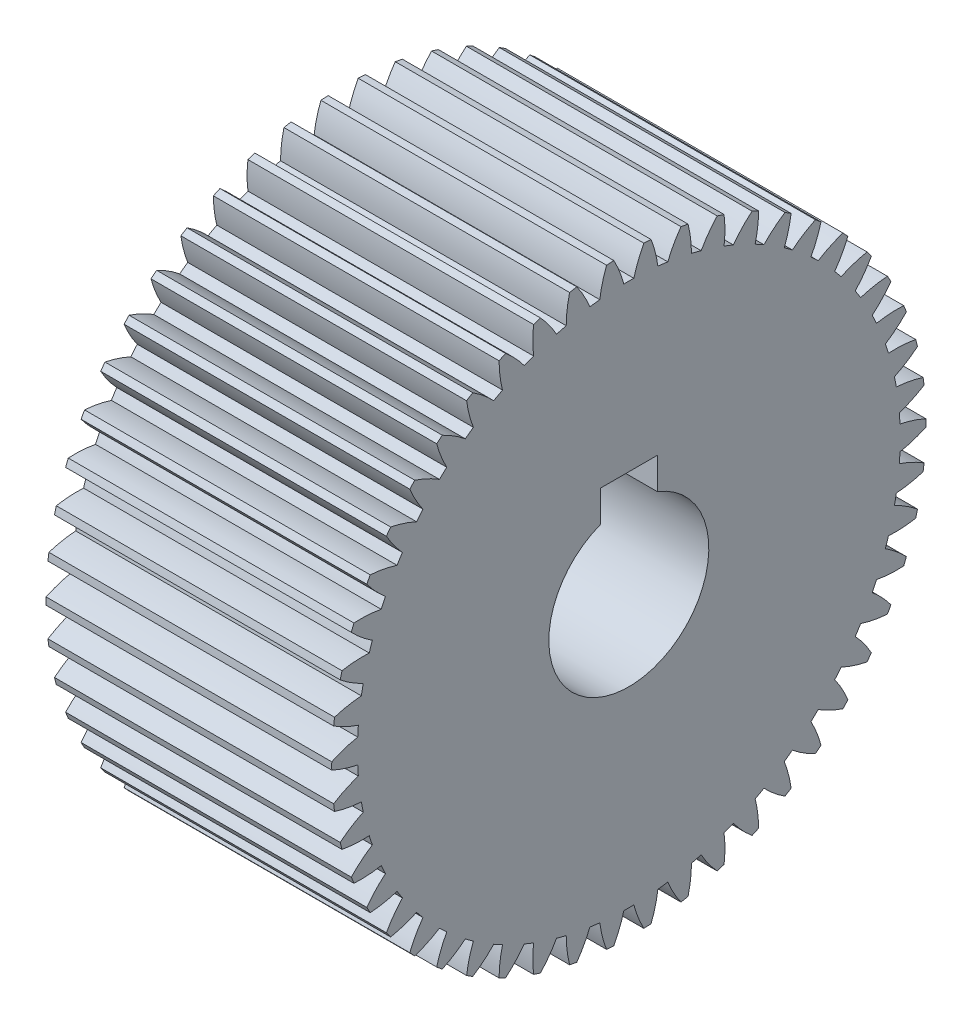
SolidWorks part; units mm, degrees
ref_plane "Plane1" through (0, 0, 0) normal (0, 0, 1) x (1, 0, 0)
ref_plane "Plane2" through (0, 0, 0) normal (0, 1, 0) x (1, 0, 0)
ref_plane "Plane3" through (0, 0, 0) normal (1, 0, 0) x (0, 0, -1)
other "Configuration Table"
sketch "HoldingSke" plane through (0, 0, 0) normal (0, 1, 0) x (1, 0, 0)
  line L0 (0, 0) -> (0.6428, -0.766)
  line L1 (-15, 0) -> (100, 0) construction
  line L2 (0, 0) -> (-2.1039, 2.3779)
  line L3 (0, 0) -> (-11.863, 4.5341)
  line L4 (0, 0) -> (5.5511, 6.6156)
  line L5 (0, 0) -> (-46.8476, -17.4728)
  line L6 (0, 0) -> (-20.7241, -13.9826)
  line L7 (-2.1039, 2.3779) -> (8.6586, 51.2059)
  line L8 (-76.2, 54.61) -> (-73.9, 54.61)
  line L9 (-71.009, 38.7566) -> (-53.1078, 45.2721)
  line L10 (-76.2, 71.12) -> (104.1128, 71.12)
  line L11 (0, 0) -> (-25, 0)
  line L12 (-76.2, 101.6) -> (-76.162, 101.6)
  line L13 (24.9733, 27.94) -> (52.9518, 28.4284)
  line L14 (24.9733, 27.94) -> (24.9743, 27.94)
  line L15 (24.9733, 27.94) -> (100.4006, 29.5858)
  line L16 (-63.627, -1) -> (-12.827, -1)
  circle A0 centre (0, 0) radius 7
  circle A1 centre (0, 0) radius 23.749
  circle A2 centre (0, 0) radius 37.5
  circle A3 centre (0, 0) radius 7
  dimension "MHD" = 47.498
  dimension "Hub_dia" = 75
  dimension "Bore" = 14
  dimension "MBD" = 14
  dimension "Num_teeth" = 50
  dimension "Pitch" = 1
  dimension "Overall_len" = 50
  dimension "Show_teeth" = 50
  dimension "Thickness" = 25
  dimension "OAL" = 50.0001
  dimension "T_dim" = 2.3
  dimension "Ap" = 20
  dimension "H" = 19.05
  dimension "Pitch_radius" = 180.3128
  dimension "Width" = 25
  dimension "Backlash" = 0.038
  dimension "Addendum_fac" = 1
  dimension "Dedendum_fac" = 1.25
  dimension "Clearance_fac" = 0.25
  dimension "Dedendum_add" = 0.001
  dimension "Module" = 1
sketch "BasProSke" plane through (0, 0, 0) normal (0, 1, 0) x (1, 0, 0)
  line L0 (-10, 0) -> (60, 0) construction
  line L1 (0, 0) -> (0, 26)
  line L2 (0, 0) -> (25, 0)
  line L3 (25, 0) -> (25, 26)
  line L4 (25, 26) -> (0, 26)
  dimension "Thickness" = 25
  dimension "Diameter" = 52
revolve "Base-Revolve" add sketch "BasProSke" angle 360 about L0
sketch "TooCutSke" plane through (0, 0, 0) normal (1, 0, 0) x (0, 0, -1)
  line L1 (0, 0) -> (0, 107) construction
  line L2 (0, 0) -> (-0.8518, 24.9855) construction
  line L3 (0, 0) -> (-3.1382, 49.8807) construction
  line L4 (-0.8518, 24.9855) -> (-1.5691, 24.9404) construction
  arc A0 (0.4377, 23.745) -> (-0.4377, 23.745) centre (0, 0) ccw
  arc A1 (1.3294, 25.9914) -> (-1.3294, 25.9914) centre (0, 0) ccw
  circle A2 centre (0, 0) radius 25 construction
  circle A3 centre (0, 0) radius 23.4923 construction
  arc A4 (-0.4377, 23.745) -> (-1.3294, 25.9914) centre (-10.1099, 21.2056) ccw
  arc A5 (1.3294, 25.9914) -> (0.4377, 23.745) centre (10.1099, 21.2056) ccw
  dimension "Root_dia" = 47.498
  dimension "Overcut_dia" = 52.0508
  dimension "Pitch_dia" = 50
  dimension "Base_dia" = 46.9846
  dimension "Flank_rad" = 10
  dimension "Half_ang" = 3.6
  dimension "Half_CT" = 0.7188
extrude "ToothCut" cut sketch "TooCutSke" along normal through all
fillet "Breaks" [suppressed] radius 0.02
fillet "RootFillets" [suppressed] radius 0.251
pattern_circular "TeethCuts" count 50 every 7.2 about axis through (-10, 0, 0) along (1, 0, 0) of "ToothCut", "RootFillets", "Breaks"
sketch "HubNeaOneSke" plane through (0, 0, 0) normal (-1, 0, 0) x (0, 0, 1)
  circle A0 centre (0, 0) radius 23.749
  dimension "Diameter" = 47.498
extrude "HubNearOne" [suppressed] add sketch "HubNeaOneSke" along normal blind 25.0001
sketch "HubNeaBotSke" plane through (0, 0, 0) normal (-1, 0, 0) x (0, 0, 1)
  circle A0 centre (0, 0) radius 23.749
  dimension "Diameter" = 47.498
extrude "HubNearBoth" [suppressed] add sketch "HubNeaBotSke" along normal blind 12.5
ref_plane "FarPln" through (25, 0, 0) normal (1, 0, 0) x (0, 0, -1)
sketch "HubFarSke" plane through (25, 0, 0) normal (1, 0, 0) x (0, 0, -1)
  circle A0 centre (0, 0) radius 23.749
  dimension "Diameter" = 47.498
extrude "HubFar" [suppressed] add sketch "HubFarSke" along normal blind 12.5
sketch "BorSke" plane through (0, 0, 0) normal (1, 0, 0) x (0, 0, -1)
  circle A0 centre (0, 0) radius 7
  dimension "Diameter" = 14
extrude "Bore" cut sketch "BorSke" along normal mid plane 100.0001
sketch "KeySke" plane through (0, 0, 0) normal (1, 0, 0) x (0, 0, -1)
  line L0 (-2.5, 0) -> (-2.5, 9.3)
  line L1 (-2.5, 9.3) -> (2.5, 9.3)
  line L2 (2.5, 9.3) -> (2.5, 0)
  line L3 (0, 0) -> (0, 34) construction
  line L4 (-2.5, 0) -> (2.5, 0)
  dimension "Offset" = 9.3
  dimension "Width" = 5
extrude "Keyway" cut sketch "KeySke" along normal mid plane 100.0001
pattern_circular "Keyway2" [suppressed] count 2 every 90 about axis through (-10, 0, 0) along (1, 0, 0)
sketch "Sketch1" plane through (0, 0, 0) normal (-1, 0, 0) x (0, 0, 1)
  circle A0 centre (0, 0) radius 25
  dimension "D1" = 50
sketch "Sketch2" plane through (25, 0, 0) normal (1, 0, 0) x (0, 0, -1)
  circle A0 centre (0, 0) radius 25
equation "' \"Module@HoldingSke\" = 6.35"
equation "' \"Num_teeth@HoldingSke\" = 12"
equation "' \"Ap@HoldingSke\" =  20"
equation "' \"Ap@HoldingSke\" = 20"
equation "' \"Width@HoldingSke\" = 0.5 * 25.4"
equation "' \"Hub_dia@HoldingSke\"= 1 * 25.4"
equation "' \"Hub_dia@HoldingSke\" = 1 * 25.4"
equation "' \"Overall_len@HoldingSke\" = 1.0 * 25.4"
equation "' \"Bore@HoldingSke\" = 0.75 * 25.4"
equation "' \"T_dim@HoldingSke\" = 0.1 * 25.4"
equation "' \"Width@KeySke\" = 0.25 * 25.4"
equation "' \"Show_teeth@HoldingSke\" = 13"
equation "' \"Backlash@HoldingSke\" = 0.009 * 25.4"
equation "' \"Addendum_fac@HoldingSke\" = 1.0"
equation "' \"Dedendum_fac@HoldingSke\" = 1.25"
equation "' \"Dedendum_add@HoldingSke\" = 0.00005 * 25.4"
equation "' \"Clearance_fac@HoldingSke\" = 0.25"
equation "\"Pitch@HoldingSke\" = 1 / \"Module@HoldingSke\""
equation "\"Overcut_dia@TooCutSke\" = (\"Num_teeth@HoldingSke\" + 2 * \"Addendum_fac@HoldingSke\") / \"Pitch@HoldingSke\" + 0.002 * 25.4"
equation "\"Pitch_dia@TooCutSke\" = \"Num_teeth@HoldingSke\" / \"Pitch@HoldingSke\""
equation "\"Base_dia@TooCutSke\" = \"Num_teeth@HoldingSke\" / \"Pitch@HoldingSke\" * cos((\"Ap@HoldingSke\"  * 3.14159265 / 180))"
equation "\"Root_dia@TooCutSke\" = (\"Num_teeth@HoldingSke\" + 2) / \"Pitch@HoldingSke\" - 2 * (\"Addendum_fac@HoldingSke\" + \"Dedendum_fac@HoldingSke\") / \"Pitch@HoldingSke\" - \"Dedendum_add@HoldingSke\" * 2"
equation "\"Half_ang@TooCutSke\" = 180 / \"Num_teeth@HoldingSke\""
equation "\"Half_CT@TooCutSke\" = \"Num_teeth@HoldingSke\" / \"Pitch@HoldingSke\" * sin((3.14159265 / 2 / \"Num_teeth@HoldingSke\")) / 2 - 7 * \"Backlash@HoldingSke\" / 4"
equation "\"Flank_rad@TooCutSke\" = \"Num_teeth@HoldingSke\" / \"Pitch@HoldingSke\" / 5"
equation "\"Radius@RootFillets\" = \"Clearance_fac@HoldingSke\" / \"Pitch@HoldingSke\" + \"Dedendum_add@HoldingSke\""
equation "\"Break_rad@Breaks\" = 0.02 / \"Pitch@HoldingSke\""
equation "\"Thickness@HoldingSke\" = \"Width@HoldingSke\""
equation "\"OAL@HoldingSke\" = \"Thickness@HoldingSke\""
equation "\"MHD@HoldingSke\" = (\"Num_teeth@HoldingSke\" + 2) / \"Pitch@HoldingSke\" - 2 * (\"Addendum_fac@HoldingSke\" + \"Dedendum_fac@HoldingSke\")  / \"Pitch@HoldingSke\" - \"Dedendum_add@HoldingSke\" * 2"
equation "\"MBD@HoldingSke\" = (\"Num_teeth@HoldingSke\" + 2) / \"Pitch@HoldingSke\" - 2 * (\"Addendum_fac@HoldingSke\" + \"Dedendum_fac@HoldingSke\")  / \"Pitch@HoldingSke\" - \"Dedendum_add@HoldingSke\" * 2 - 0.002 * 25.4"
equation "\"MHD@HoldingSke\" = ((sgn( \"MHD@HoldingSke\" - \"Hub_dia@HoldingSke\" )-1)*( \"MHD@HoldingSke\" - \"Hub_dia@HoldingSke\" ))/-2+ \"Hub_dia@HoldingSke\""
equation "\"MBD@HoldingSke\" = ((sgn( \"MBD@HoldingSke\" - \"Bore@HoldingSke\" )-1)*( \"MBD@HoldingSke\" - \"Bore@HoldingSke\" ))/-2+ \"Bore@HoldingSke\""
equation "\"OAL@HoldingSke\" = ((sgn( \"OAL@HoldingSke\" - \"Overall_len@HoldingSke\" )+1)*( \"OAL@HoldingSke\" - \"Overall_len@HoldingSke\" ))/2 + \"Overall_len@HoldingSke\" + 0.000002 * 25.4"
equation "\"Num_teeth@TeethCuts\" = int( \"Show_teeth@HoldingSke\" ) + 1"
equation "\"Num_teeth@TeethCuts\" = ((sgn( \"Num_teeth@TeethCuts\" - \"Num_teeth@HoldingSke\" )-1)*( \"Num_teeth@TeethCuts\" - \"Num_teeth@HoldingSke\" ))/-2+ \"Num_teeth@HoldingSke\""
equation "\"Num_teeth@TeethCuts\" = ((sgn( \"Num_teeth@TeethCuts\" - 2.0)+1)*( \"Num_teeth@TeethCuts\" - 2.0))/2 +2.0"
equation "\"Angle@TeethCuts\" = 360.0 / \"Num_teeth@HoldingSke\""
equation "\"Diameter@BasProSke\" = (\"Num_teeth@HoldingSke\" + 2 * \"Addendum_fac@HoldingSke\") / \"Pitch@HoldingSke\""
equation "\"Thickness@BasProSke\"  = \"Thickness@HoldingSke\""
equation "' \"Fillet_rad@BasProSke\" =  \"Thickness@HoldingSke\" * 0.05"
equation "' \"Fillet_rad@BasProSke\" = \"Thickness@HoldingSke\" * 0.05"
equation "\"MHD@HoldingSke\" = ((sgn( \"MHD@HoldingSke\" - \"Root_dia@TooCutSke\" )-1)*( \"MHD@HoldingSke\" - \"Root_dia@TooCutSke\" ))/-2+ \"Root_dia@TooCutSke\""
equation "\"Diameter@HubNeaOneSke\" = \"MHD@HoldingSke\""
equation "\"Length@HubNearOne\" = \"OAL@HoldingSke\" - \"Thickness@BasProSke\""
equation "\"Diameter@HubNeaBotSke\" = \"MHD@HoldingSke\""
equation "\"Length@HubNearBoth\" = ( \"OAL@HoldingSke\" - \"Thickness@BasProSke\" ) / 2.0"
equation "\"Thickness@FarPln\" = \"Thickness@BasProSke\""
equation "\"Diameter@HubFarSke\" = \"MHD@HoldingSke\""
equation "\"Length@HubFar\" = ( \"OAL@HoldingSke\" - \"Thickness@BasProSke\" ) / 2.0"
equation "\"Diameter@BorSke\" = \"MBD@HoldingSke\""
equation "\"D1@Bore\" = \"OAL@HoldingSke\" * 2.0"
equation "\"D1@Keyway\" = \"OAL@HoldingSke\" * 2.0"
equation "\"Offset@KeySke\" = \"T_dim@HoldingSke\" + \"MBD@HoldingSke\" / 2.0"
